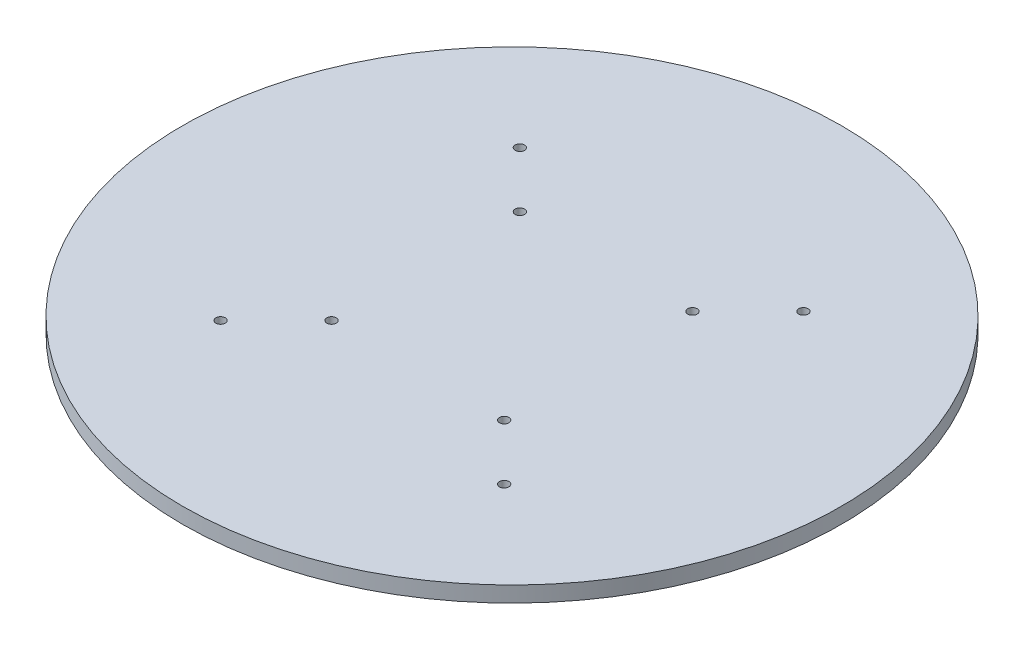
SolidWorks part; units mm, degrees
ref_plane "Front Plane" through (0, 0, 0) normal (0, 0, 1) x (1, 0, 0)
ref_plane "Top Plane" through (0, 0, 0) normal (0, 1, 0) x (1, 0, 0)
ref_plane "Right Plane" through (0, 0, 0) normal (1, 0, 0) x (0, 0, -1)
sketch "Sketch1" plane through (0, 0, 0) normal (0, 1, 0) x (1, 0, 0)
  line L0 (0, -55) -> (0, 55) construction
  line L1 (-55, 0) -> (55, 0) construction
  line L2 (-27.5, 30) -> (-45.1777, 47.6777) construction
  circle A0 centre (0, 0) radius 105
  circle A1 centre (-27.5, 30) radius 1.5
  circle A2 centre (27.5, 30) radius 1.5
  circle A3 centre (27.5, -30) radius 1.5
  circle A4 centre (-27.5, -30) radius 1.5
  circle A5 centre (-45.1777, 47.6777) radius 1.5
  circle A6 centre (45.1777, 47.6777) radius 1.5
  circle A7 centre (45.1777, -47.6777) radius 1.5
  circle A8 centre (-45.1777, -47.6777) radius 1.5
  dimension "D1" = 210
  dimension "D2" = 3
  dimension "D5" = 3
  dimension "D3" = 27.5
  dimension "D4" = 30
  dimension "D6" = 25
  dimension "D7" = 45
extrude "Boss-Extrude1" add sketch "Sketch1" along normal blind 5
